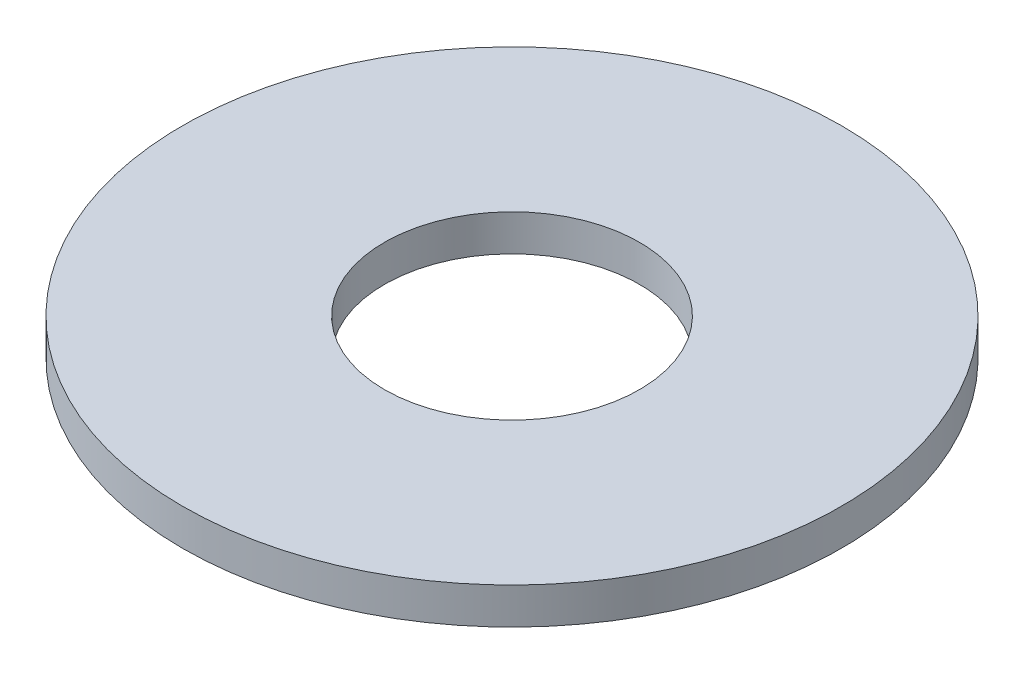
SolidWorks part; units mm, degrees
material "Alloy Steel (SS)"
ref_plane "Front Plane" through (0, 0, 0) normal (0, 0, 1) x (1, 0, 0)
ref_plane "Top Plane" through (0, 0, 0) normal (0, 1, 0) x (1, 0, 0)
ref_plane "Right Plane" through (0, 0, 0) normal (1, 0, 0) x (0, 0, -1)
sketch "Sketch1" plane through (0, 0, 0) normal (0, 1, 0) x (1, 0, 0)
  circle A0 centre (0, 0) radius 14.351
extrude "Boss-Extrude1" add sketch "Sketch1" along normal blind 1.5875 contours A0
sketch "Sketch2" plane through (0, 1.5875, 0) normal (0, 1, 0) x (1, 0, 0)
  circle A0 centre (0, 0) radius 5.5562
extrude "Cut-Extrude1" cut sketch "Sketch2" against normal through all
